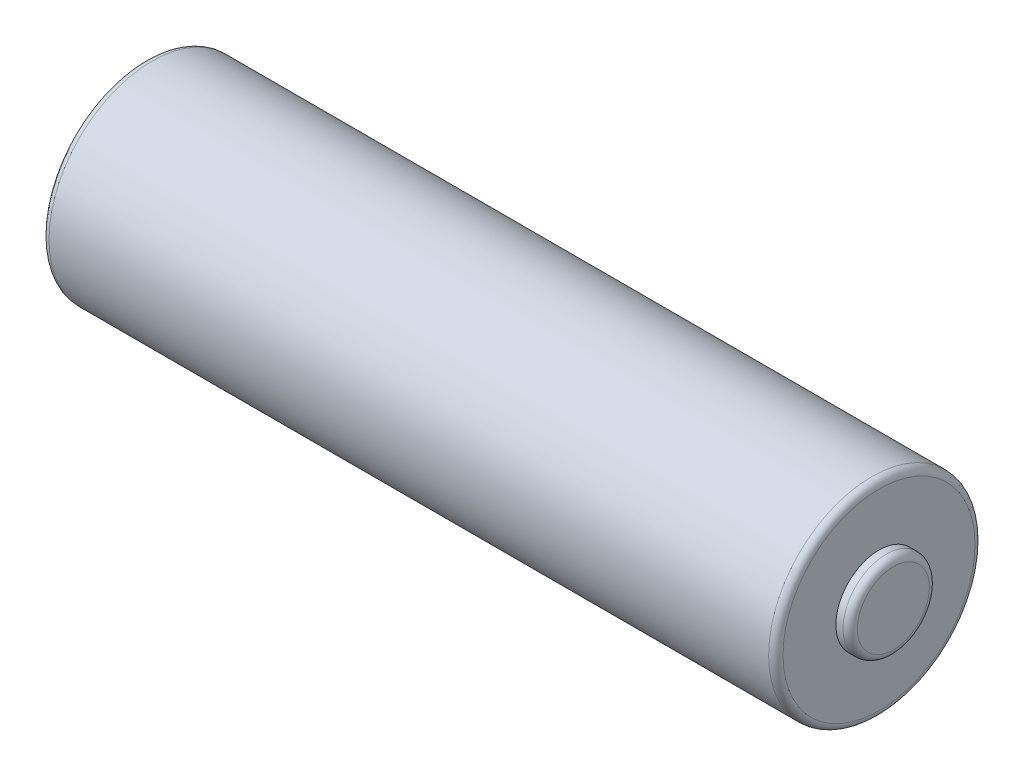
SolidWorks part; units mm, degrees
ref_plane "Front Plane" through (0, 0, 0) normal (0, 0, 1) x (1, 0, 0)
ref_plane "Top Plane" through (0, 0, 0) normal (0, 1, 0) x (1, 0, 0)
ref_plane "Right Plane" through (0, 0, 0) normal (1, 0, 0) x (0, 0, -1)
sketch "Sketch1" plane through (0, 0, 0) normal (1, 0, 0) x (0, 0, -1)
  circle A0 centre (0, 0) radius 7.17
  dimension "D1" = 14.34
extrude "Boss-Extrude1" add sketch "Sketch1" along normal mid plane 51
sketch "Sketch2" plane through (25.5, 0, 0) normal (1, 0, 0) x (0, 0, -1)
  circle A0 centre (0, 0) radius 3
  dimension "D1" = 6
extrude "Boss-Extrude2" add sketch "Sketch2" along normal blind 1
fillet "Fillet1" radius 0.5 3 edges at (26.5, 0, -3) (-25.5, 0, -7.17) (25.5, 0, -7.17)
